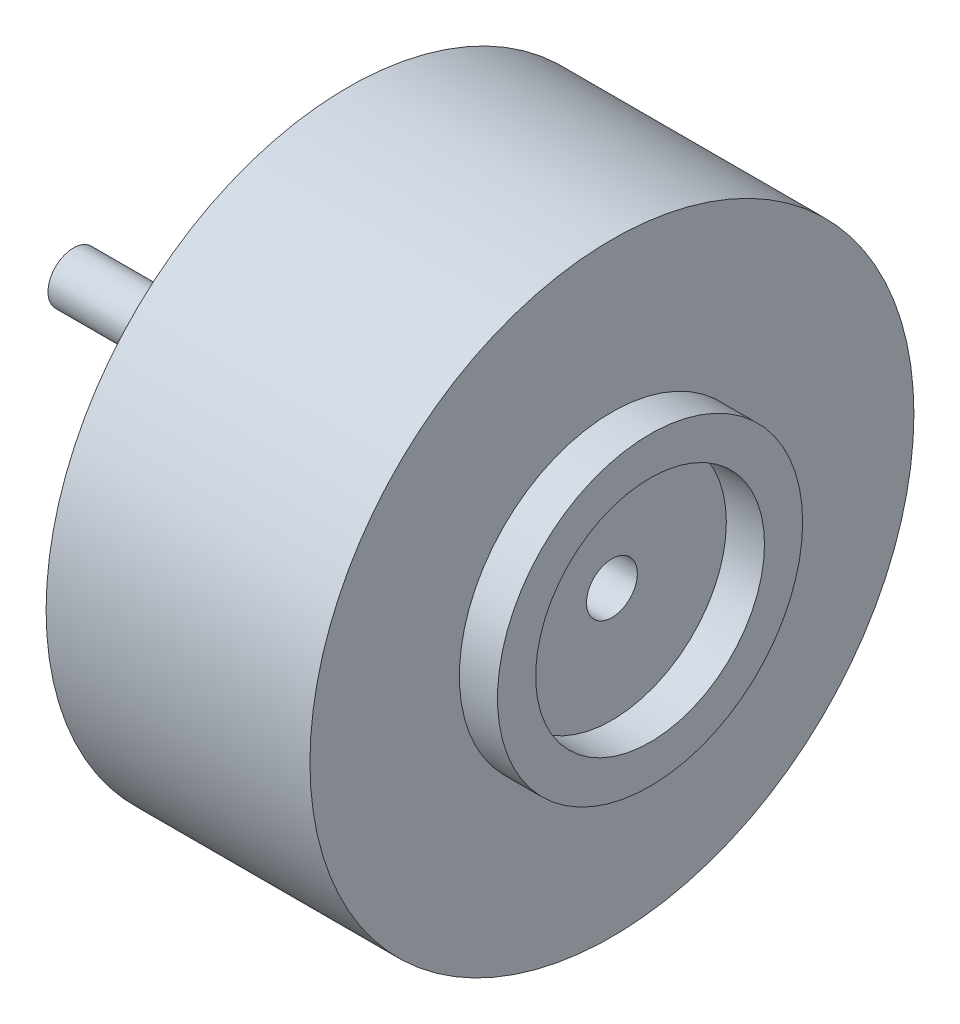
SolidWorks part; units mm, degrees
ref_plane "Front Plane" through (0, 0, 0) normal (0, 0, 1) x (1, 0, 0)
ref_plane "Top Plane" through (0, 0, 0) normal (0, 1, 0) x (1, 0, 0)
ref_plane "Right Plane" through (0, 0, 0) normal (1, 0, 0) x (0, 0, -1)
sketch "Sketch1" plane through (0, 0, 0) normal (1, 0, 0) x (0, 0, -1)
  circle A0 centre (0, 0) radius 23.75
  circle A1 centre (0, 0) radius 3
extrude "Boss-Extrude1" add sketch "Sketch1" along normal blind 20.75
sketch "Sketch4" plane through (20.75, 0, 0) normal (1, 0, 0) x (0, 0, -1)
  circle A0 centre (0, 0) radius 3
  circle A1 centre (0, 0) radius 2
extrude "Boss-Extrude2" add sketch "Sketch4" against normal blind 20.75
sketch "Sketch5" plane through (20.75, 0, 0) normal (1, 0, 0) x (0, 0, -1)
  circle A0 centre (0, 0) radius 12
  circle A1 centre (0, 0) radius 9
extrude "Boss-Extrude3" add sketch "Sketch5" along normal blind 3
sketch "Sketch6" plane through (0, 0, 0) normal (1, 0, 0) x (0, 0, -1)
  circle A0 centre (0, 0) radius 12
  circle A1 centre (0, 0) radius 9
extrude "Boss-Extrude4" add sketch "Sketch6" against normal blind 3
sketch "Sketch7" plane through (0, 0, 0) normal (1, 0, 0) x (0, 0, -1)
  circle A0 centre (0, 0) radius 1
  circle A1 centre (0, 0) radius 2
extrude "Boss-Extrude6" add sketch "Sketch7" against normal blind 21.6 separate body
